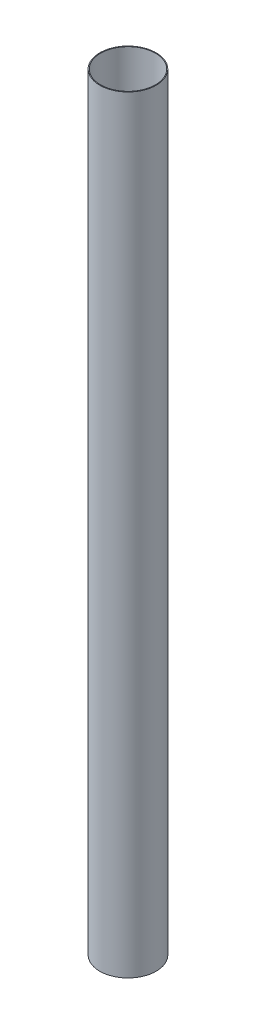
SolidWorks part; units mm, degrees
material "Hexcel AS4C (3000 Filaments)"
ref_plane "Front Plane" through (0, 0, 0) normal (0, 0, 1) x (1, 0, 0)
ref_plane "Top Plane" through (0, 0, 0) normal (0, 1, 0) x (1, 0, 0)
ref_plane "Right Plane" through (0, 0, 0) normal (1, 0, 0) x (0, 0, -1)
sketch "Sketch2" plane through (0, 0, 0) normal (0, 1, 0) x (1, 0, 0)
  circle A0 centre (0, 0) radius 76.2
  circle A1 centre (0, 0) radius 78.359
  dimension "D1" = 152.4
  dimension "D2" = 156.718
extrude "Boss-Extrude1" add sketch "Sketch2" along normal blind 2133.6
equation "\"CF_OD_A\"= 4.015in"
equation "\"CF_ID_A\"= 3.904in"
equation "\"KF_ID_A\"= 4.015in ' Kevlar airframe ID"
equation "\"CF_OD_C\"= 3.894in ' VERIFY Coupler OD"
equation "\"CF_ID_C\"= 3.783in ' VERIFY Coupler ID"
equation "\"KF_WALL\"= 0.0625in"
equation "\"AF_01\"=10in"
equation "\"AF_02\"=16in"
equation "\"AF_03\"=in"
equation "\"B_CF_OD\"=6.17in"
equation "\"B_CF_ID\"=6in"
equation "\"B_CF_WT\"=0.085in"
equation "\"D1@Sketch2\"=\"B_CF_ID\""
equation "\"D2@Sketch2\"=\"B_CF_OD\""
